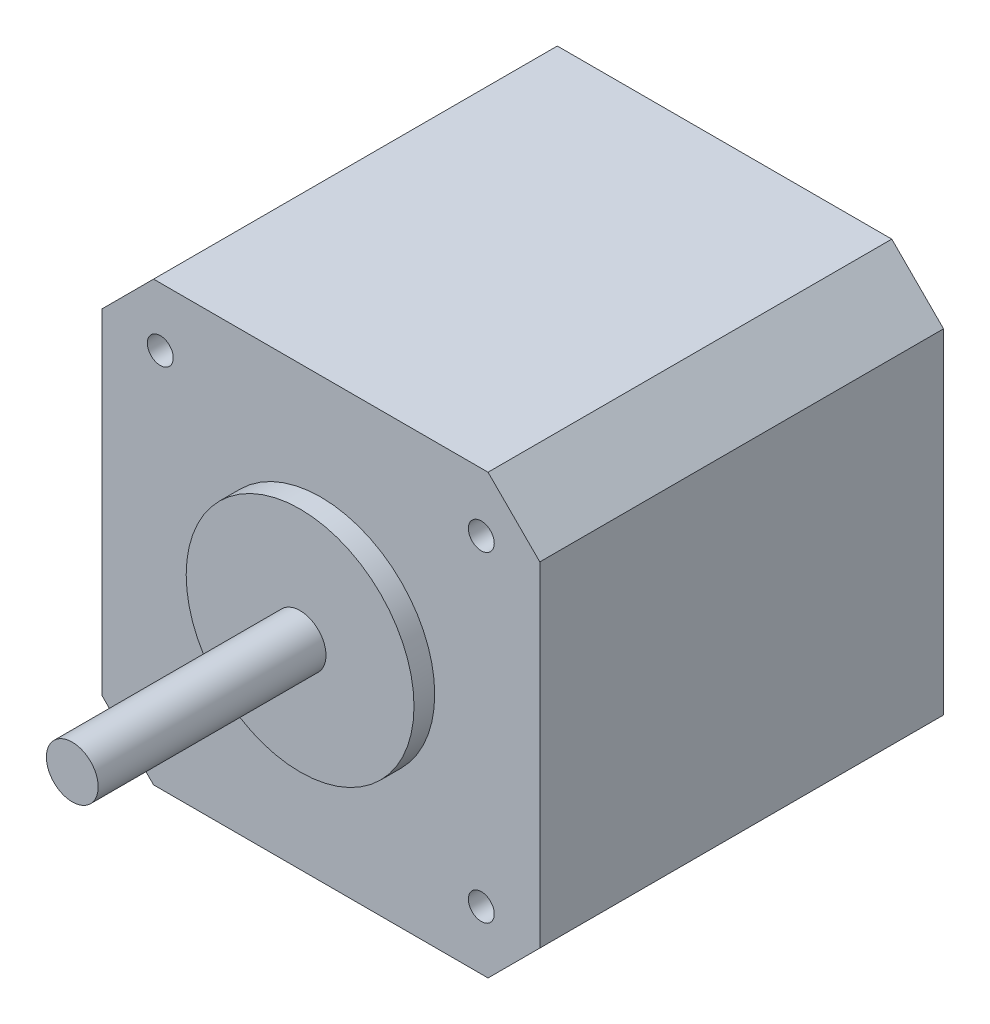
SolidWorks part; units mm, degrees
ref_plane "Front Plane" through (0, 0, 0) normal (0, 0, 1) x (1, 0, 0)
ref_plane "Top Plane" through (0, 0, 0) normal (0, 1, 0) x (1, 0, 0)
ref_plane "Right Plane" through (0, 0, 0) normal (1, 0, 0) x (0, 0, -1)
sketch "Sketch1" plane through (0, 0, 0) normal (0, 0, 1) x (1, 0, 0)
  line L0 (0, 37.3) -> (5, 42.3)
  line L1 (5, 0) -> (37.3, 0)
  line L2 (0, 5) -> (0, 37.3)
  line L3 (5, 42.3) -> (37.3, 42.3)
  line L4 (42.3, 5) -> (42.3, 37.3)
  line L5 (37.3, 42.3) -> (42.3, 37.3)
  line L6 (37.3, 0) -> (42.3, 5)
  line L7 (0, 5) -> (5, 0)
  point P0 (0, 0)
  point P1 (42.3, 42.3)
  point P2 (0, 42.3)
  point P3 (42.3, 0)
  dimension "D1" = 42.3
extrude "Boss-Extrude1" add sketch "Sketch1" along normal blind 38.989
hole_wizard "M3x0.5 Tapped Hole1" positions "Sketch3" profile "Sketch2" tap size "M3x0.5" standard "ANSI Metric"
sketch "Sketch3" plane through (0, 0, 38.989) normal (0, 0, 1) x (1, 0, 0)
  line L0 (21.15, 42.3) -> (21.15, 0) construction
  line L1 (37.3, 42.3) -> (5, 42.3) construction
  line L2 (5, 0) -> (37.3, 0) construction
  line L5 (0, 21.15) -> (42.3, 21.15) construction
  line L6 (0, 37.3) -> (0, 5) construction
  line L7 (42.3, 5) -> (42.3, 37.3) construction
  line L11 (5.65, 5.65) -> (36.65, 5.65)
  line L12 (5.65, 5.65) -> (5.65, 36.65)
  line L13 (5.65, 36.65) -> (36.65, 36.65)
  line L14 (36.65, 5.65) -> (36.65, 36.65)
  line L15 (5.65, 5.65) -> (36.65, 36.65) construction
  line L16 (5.65, 36.65) -> (36.65, 5.65) construction
  point P0 (5.65, 36.65)
  point P2 (36.65, 36.65)
  point P4 (36.65, 5.65)
  point P6 (5.65, 5.65)
  dimension "D1" = 31
  dimension "D2" = 31
sketch "Sketch2" plane through (5.65, 36.65, 38.989) normal (1, 0, 0) x (0, -1, 0)
  line L0 (0, 0) -> (0, 5.7511)
  line L1 (0, 5.7511) -> (1.25, 5)
  line L2 (1.25, 5) -> (1.25, 0)
  line L5 (1.25, 0) -> (0, 0)
  line L10 (0, 5.7511) -> (-1.25, 5) construction
  line L11 (0, -6.35) -> (0, 107.95) construction
  dimension "Tap Drill Dia." = 2.5
  dimension "Tap Drill Depth" = 5
  dimension "Drill Angle" = 118
cosmetic thread "Hole Thread1" parameters "D1"=5, "D2"=3
cosmetic thread "Hole Thread2" parameters "D1"=5, "D2"=3
cosmetic thread "Hole Thread3" parameters "D1"=5, "D2"=3
cosmetic thread "Hole Thread4" parameters "D1"=5, "D2"=3
sketch "Sketch4" plane through (0, 0, 38.989) normal (0, 0, 1) x (1, 0, 0)
  line L0 (0, 21.15) -> (42.3, 21.15) construction
  line L1 (21.15, 42.3) -> (21.15, 0) construction
  line L2 (0, 21.15) -> (42.3, 21.15) construction
  line L3 (21.15, 42.3) -> (21.15, 0) construction
  circle A0 centre (21.15, 21.15) radius 11
  dimension "D1" = 22
extrude "Boss-Extrude2" add sketch "Sketch4" along normal blind 2
sketch "Sketch5" plane through (0, 0, 40.989) normal (0, 0, 1) x (1, 0, 0)
  line L0 (0, 21.15) -> (42.3, 21.15) construction
  line L1 (21.15, 42.3) -> (21.15, 0) construction
  line L2 (0, 21.15) -> (42.3, 21.15) construction
  line L3 (21.15, 42.3) -> (21.15, 0) construction
  circle A0 centre (21.15, 21.15) radius 2.5
  dimension "D1" = 5
extrude "Boss-Extrude3" add sketch "Sketch5" along normal blind 22 contours A0
